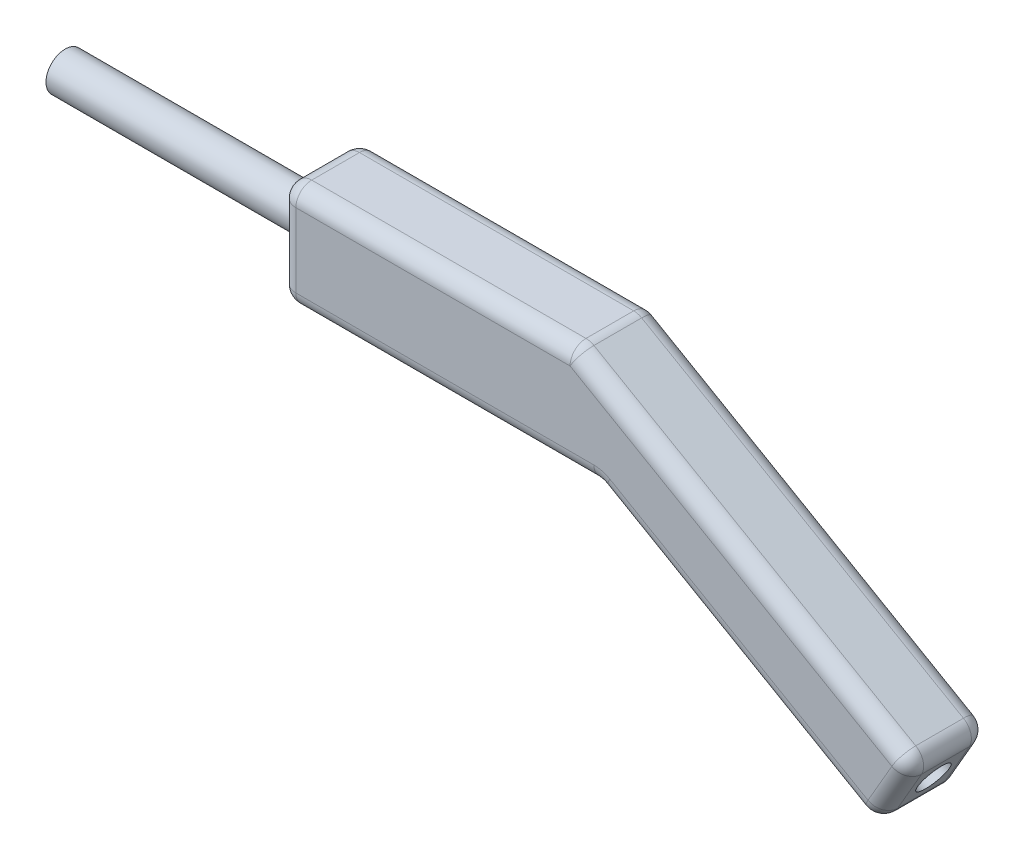
SolidWorks part; units mm, degrees
ref_plane "前视基准面" through (0, 0, 0) normal (0, 0, 1) x (1, 0, 0)
ref_plane "上视基准面" through (0, 0, 0) normal (0, 1, 0) x (1, 0, 0)
ref_plane "右视基准面" through (0, 0, 0) normal (1, 0, 0) x (0, 0, -1)
sketch "草图1" plane through (0, 0, 0) normal (0, 0, 1) x (1, 0, 0)
  line L0 (1.3154, 1.5367) -> (11.9757, -4.618)
  line L1 (-7.9346, 1.5367) -> (1.3154, 1.5367)
  line L2 (-7.9346, 1.5367) -> (-7.9346, -1.783)
  line L3 (-7.9346, -1.783) -> (2.0654, -1.783)
  line L5 (-7.9346, 1.5367) -> (2.0654, -1.783) construction
  line L6 (-7.9346, -1.783) -> (1.3154, 1.5367) construction
  line L7 (2.0654, -1.783) -> (10.7257, -6.783)
  line L8 (10.7257, -6.783) -> (11.9757, -4.618)
  point P0 (-3.1294, -0.0585)
  dimension "D1" = 2.5
  dimension "D2" = 10
  dimension "D4" = 10
extrude "凸台-拉伸1" add sketch "草图1" along normal blind 2.5
sketch "草图2" plane through (10.9814, -6.3401, 0) normal (0.866, -0.5, 0) x (0, 0, -1)
  line L0 (-2.5, 1.9886) -> (0, -0.5114) construction
  line L1 (0, -0.5114) -> (0, 1.9886) construction
  line L2 (0, 1.9886) -> (-2.5, -0.5114) construction
  circle A0 centre (-1.25, 0.7386) radius 0.5
  dimension "D1" = 1
extrude "切除-拉伸1" cut sketch "草图2" against normal blind 8
sketch "草图3" plane through (-7.9346, 0, 0) normal (-1, 0, 0) x (0, 0, 1)
  line L0 (0, 1.5367) -> (2.5, -1.783) construction
  line L1 (2.5, 1.5367) -> (0, -1.783) construction
  circle A0 centre (1.25, -0.1231) radius 0.6
  dimension "D1" = 1.2
extrude "凸台-拉伸2" add sketch "草图3" along normal blind 8
fillet "圆角1" radius 0.5 18 edges at (-7.9346, 1.5367, 1.25) (11.9757, -4.618, 1.25) (10.7257, -6.783, 1.25) (11.3507, -5.7005, 2.5) (6.3956, -4.283, 0) (6.3956, -4.283, 2.5) (6.6456, -1.5406, 0) (6.6456, -1.5406, 2.5) (1.3154, 1.5367, 1.25) (-2.9346, -1.783, 2.5) (-3.3096, 1.5367, 2.5) (-2.9346, -1.783, 0) (-3.3096, 1.5367, 0) (-7.9346, -0.1231, 0) (-7.9346, -1.783, 1.25) (-7.9346, -0.1231, 2.5) (2.0654, -1.783, 1.25) (11.3507, -5.7005, 0)
